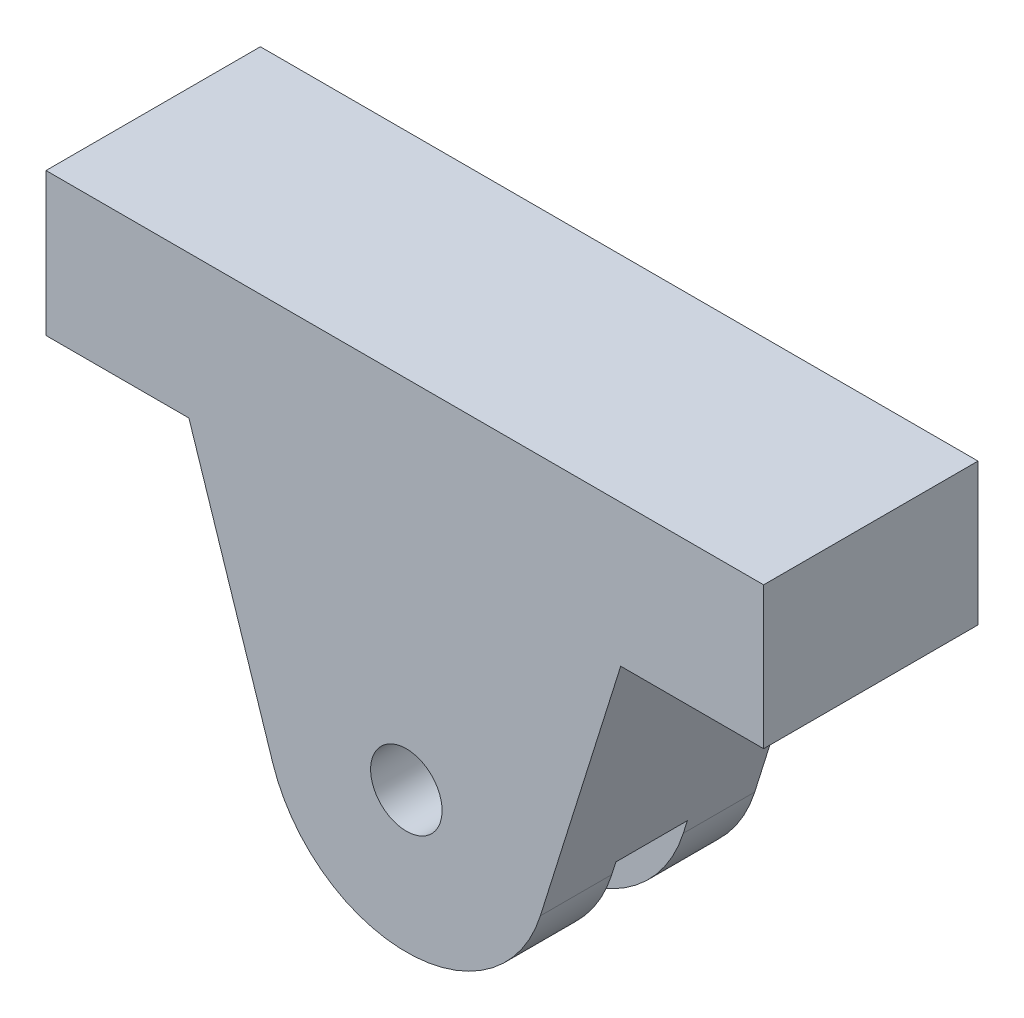
SolidWorks part; units mm, degrees
ref_plane "Plane1" through (0, 0, 0) normal (0, 0, 1) x (1, 0, 0)
ref_plane "Plane2" through (0, 0, 0) normal (0, 1, 0) x (1, 0, 0)
ref_plane "Plane3" through (0, 0, 0) normal (1, 0, 0) x (0, 0, -1)
other "Configuration Table"
sketch "Sketch1" plane through (0, 0, 0) normal (0, 0, 1) x (1, 0, 0)
  line L0 (30.4261, 20.1391) -> (19.1804, -15.7392)
  line L1 (-50, 40) -> (50.4261, 40)
  line L2 (-50, 40) -> (-50, 20)
  line L3 (50.4261, 20.1391) -> (30.4261, 20.1391)
  line L4 (50.4261, 40) -> (50.4261, 20.1391)
  line L5 (-30, 20) -> (-18.257, -15.9617)
  line L6 (-50, 20) -> (-30, 20)
  arc A0 (-18.257, -15.9617) -> (19.1804, -15.7392) centre (0.4261, -9.8609) ccw
  circle A1 centre (0.4261, -9.8609) radius 5
  dimension "D1" = 10
extrude "Base-Extrude" add sketch "Sketch1" along normal mid plane 30
sketch "Sketch2" plane through (0, 0, 0) normal (0, 0, 1) x (1, 0, 0)
  line L0 (-50.1484, -40) -> (50, -40)
  line L1 (50, -40) -> (6.4566, -2.4674)
  line L2 (-50.1484, -40) -> (-6.6009, -2.4671)
  arc A0 (6.4566, -2.4674) -> (-6.6009, -2.4671) centre (-0.0723, -10.0419) ccw
  dimension "D1" = 57.4867
  dimension "D2" = 57.49
extrude "Cut-Extrude1" cut sketch "Sketch2" against normal mid plane 10
